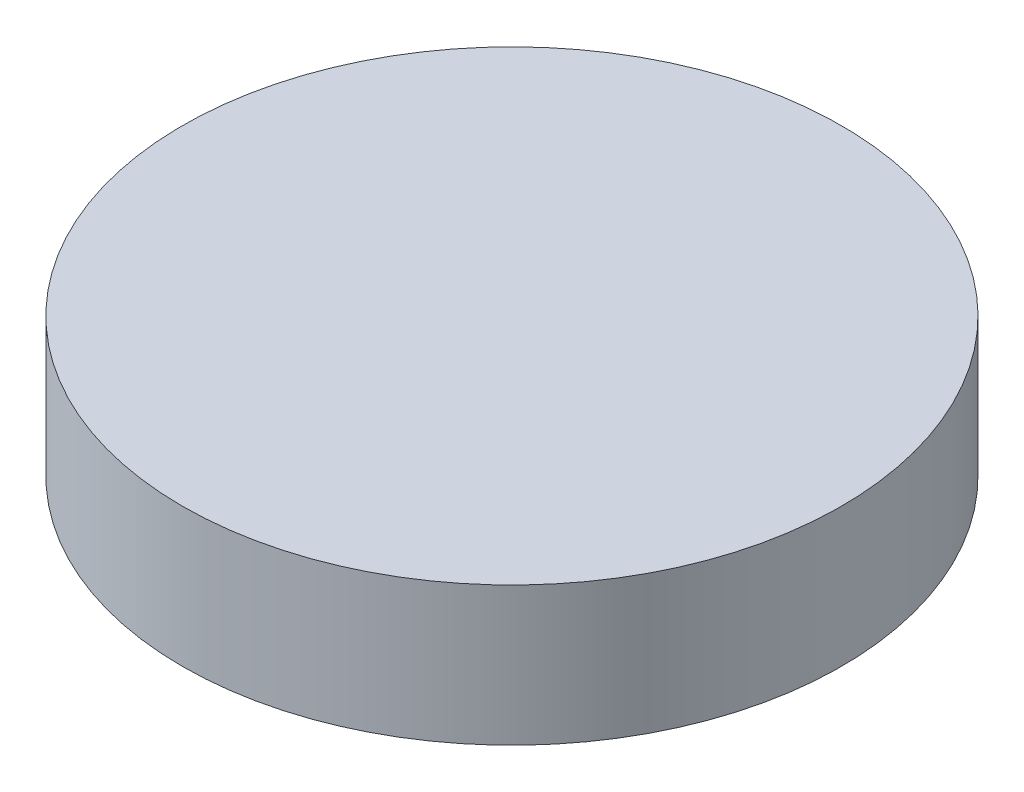
SolidWorks part; units mm, degrees
material "Borracha"
ref_plane "Plano frontal" through (0, 0, 0) normal (0, 0, 1) x (1, 0, 0)
ref_plane "Plano superior" through (0, 0, 0) normal (0, 1, 0) x (1, 0, 0)
ref_plane "Plano direito" through (0, 0, 0) normal (1, 0, 0) x (0, 0, -1)
sketch "Esboço1" plane through (0, 0, 0) normal (0, 1, 0) x (1, 0, 0)
  circle A0 centre (0, 0) radius 9.5
extrude "Ressalto-extrusão1" add sketch "Esboço1" along normal blind 4
